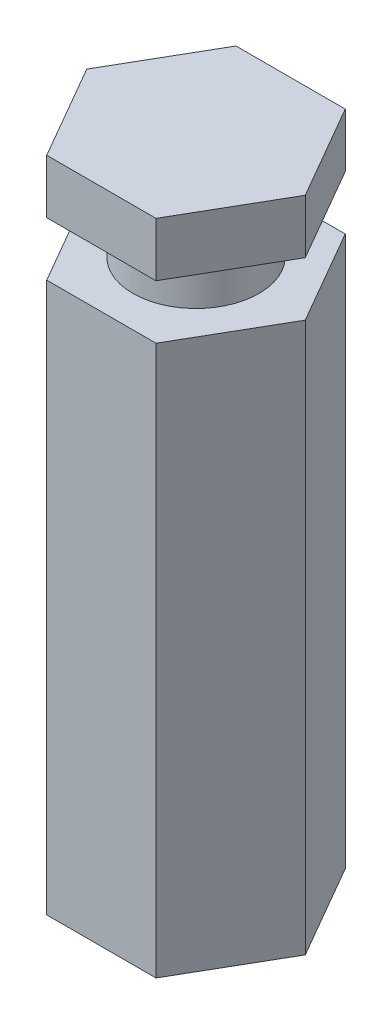
SolidWorks part; units mm, degrees
ref_plane "Front Plane" through (0, 0, 0) normal (0, 0, 1) x (1, 0, 0)
ref_plane "Top Plane" through (0, 0, 0) normal (0, 1, 0) x (1, 0, 0)
ref_plane "Right Plane" through (0, 0, 0) normal (1, 0, 0) x (0, 0, -1)
sketch "Sketch1" plane through (0, 0, 0) normal (0, 1, 0) x (1, 0, 0)
  line L1 (-12.1244, 0) -> (-6.0622, -10.5)
  line L2 (-6.0622, -10.5) -> (6.0622, -10.5)
  line L3 (6.0622, -10.5) -> (12.1244, 0)
  line L4 (12.1244, 0) -> (6.0622, 10.5)
  line L5 (6.0622, 10.5) -> (-6.0622, 10.5)
  line L6 (-6.0622, 10.5) -> (-12.1244, 0)
  circle A0 centre (0, 0) radius 10.5 construction
  dimension "D1" = 21
extrude "Boss-Extrude1" add sketch "Sketch1" along normal blind 61
sketch "Sketch2" plane through (0, 61, 0) normal (0, 1, 0) x (1, 0, 0)
  circle A0 centre (0, 0) radius 7
extrude "Boss-Extrude2" add sketch "Sketch2" along normal blind 6
sketch "Sketch3" plane through (0, 67, 0) normal (0, 1, 0) x (1, 0, 0)
  line L1 (-12.1244, 0) -> (-6.0622, -10.5)
  line L2 (-6.0622, -10.5) -> (6.0622, -10.5)
  line L3 (6.0622, -10.5) -> (12.1244, 0)
  line L4 (12.1244, 0) -> (6.0622, 10.5)
  line L5 (6.0622, 10.5) -> (-6.0622, 10.5)
  line L6 (-6.0622, 10.5) -> (-12.1244, 0)
  circle A0 centre (0, 0) radius 10.5 construction
  dimension "D1" = 21
extrude "Boss-Extrude3" add sketch "Sketch3" along normal blind 6
